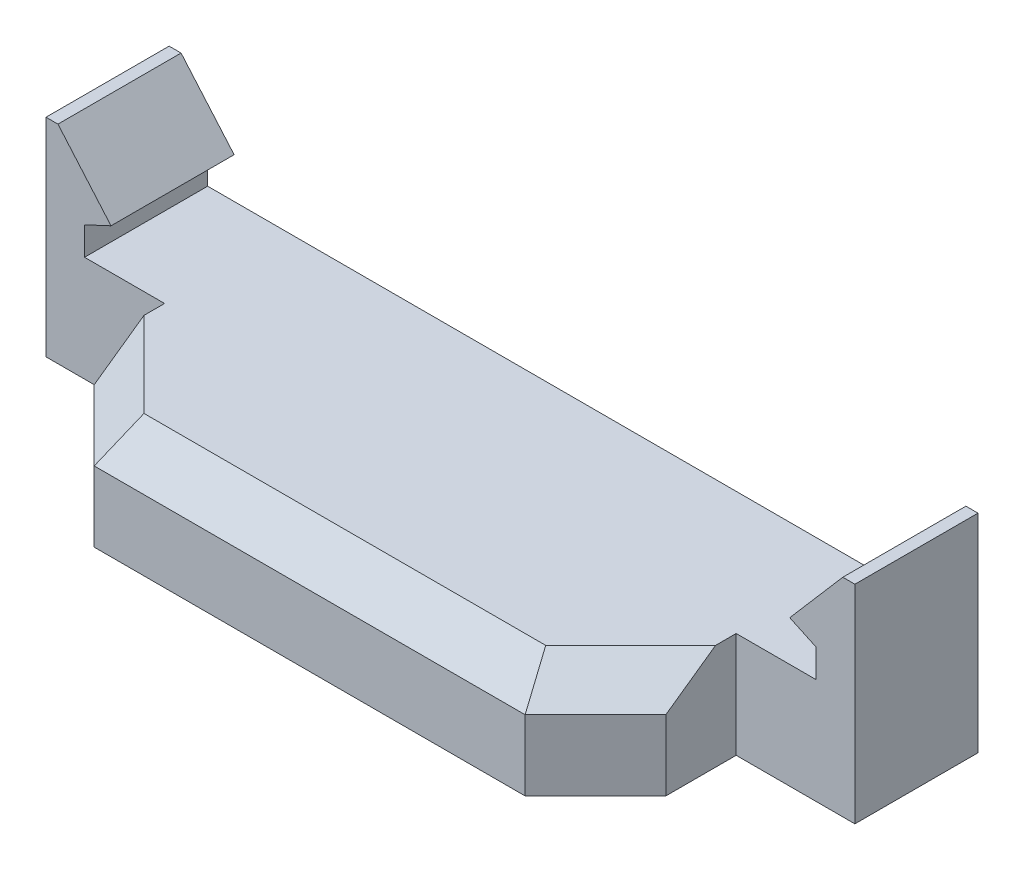
SolidWorks part; units mm, degrees
ref_plane "Plano frontal" through (0, 0, 0) normal (0, 0, 1) x (1, 0, 0)
ref_plane "Plano superior" through (0, 0, 0) normal (0, 1, 0) x (1, 0, 0)
ref_plane "Plano direito" through (0, 0, 0) normal (1, 0, 0) x (0, 0, -1)
sketch "Esboço2" plane through (0, 0, 0) normal (0, 0, 1) x (1, 0, 0)
  line L0 (11.1561, 4.4006) -> (12, 4.4006)
  line L1 (-11.996, 1.5) -> (12.25, 1.5)
  line L2 (-12.25, 1.5) -> (-12.25, -1.5) construction
  line L3 (-11.996, -1.5) -> (12, -1.5)
  line L4 (12.25, 1.5) -> (12.25, -1.5) construction
  line L5 (-12.25, 1.5) -> (12.25, -1.5) construction
  line L6 (-12.25, -1.5) -> (12.25, 1.5) construction
  line L7 (11.1561, 4.4006) -> (9.6482, 2.6506)
  line L8 (9.6482, 2.6506) -> (10.4, 2.3)
  line L9 (10.4, 2.3) -> (10.4, 1.5)
  line L10 (10.4, 2.3) -> (7.7733, 2.3) construction
  line L11 (0, -9.2019) -> (0, 6.2019) construction
  line L12 (12.25, 4.2917) -> (12.25, 1.5) construction
  line L13 (-10.4, 2.3) -> (-7.7733, 2.3) construction
  line L14 (-12.25, 4.2917) -> (-12.25, 1.5) construction
  line L15 (-10.4, 2.3) -> (-10.4, 1.5)
  line L16 (-9.6482, 2.6506) -> (-10.4, 2.3)
  line L17 (-11.1561, 4.4006) -> (-9.6482, 2.6506)
  line L18 (12.25, 1.5) -> (12.25, -1.5) construction
  line L19 (-11.1561, 4.4006) -> (-11.996, 4.4006)
  line L20 (12, -1.5) -> (12, 4.4006)
  line L21 (-11.996, -1.5) -> (-11.996, 4.4006)
  point P0 (0, 0)
  point P14 (0, -1.5)
  point P24 (0, 0)
  point P25 (9.6482, 2.6506)
  dimension "D1" = 3.1
  dimension "D2" = 24.5
  dimension "D3" = 25
  dimension "D4" = 3
  dimension "D5" = 2.31
  dimension "D6" = 0.8
  dimension "D7" = 1.85
  dimension "D8" = 0.25
  dimension "D9" = 0.254
extrude "Ressalto-extrusão1" add sketch "Esboço2" along normal blind 3.5
sketch "Esboço3" plane through (12, 0, 0) normal (1, 0, 0) x (0, 0, -1)
  line L4 (0, -1.5) -> (0, 4.4006)
  line L5 (0, 4.4006) -> (-3.5, 4.4006)
  line L6 (-3.5, 4.4006) -> (-3.5, -1.5)
  line L7 (-3.5, -1.5) -> (0, -1.5)
  line L8 (0, -1.5) -> (0, 4.4006)
  line L9 (0, 4.4006) -> (-3.5, 4.4006)
  line L10 (-3.5, 4.4006) -> (-3.5, -1.5)
  line L11 (-3.5, -1.5) -> (0, -1.5)
  dimension "D1" = 0
extrude "Corte-extrusão1" cut sketch "Esboço3" against normal blind 0.5
sketch "Esboço4" plane through (-11.996, 0, 0) normal (-1, 0, 0) x (0, 0, 1)
  line L4 (0, 4.4006) -> (0, -1.5)
  line L5 (0, -1.5) -> (3.5, -1.5)
  line L6 (3.5, -1.5) -> (3.5, 4.4006)
  line L7 (3.5, 4.4006) -> (0, 4.4006)
  line L8 (0, 4.4006) -> (0, -1.5)
  line L9 (0, -1.5) -> (3.5, -1.5)
  line L10 (3.5, -1.5) -> (3.5, 4.4006)
  line L11 (3.5, 4.4006) -> (0, 4.4006)
  dimension "D1" = 0
extrude "Corte-extrusão2" cut sketch "Esboço4" against normal blind 0.5
sketch "Esboço5" plane through (0, 0, 3.5) normal (0, 0, 1) x (1, 0, 0)
  line L0 (-11.496, -1.5) -> (11.5, -1.5) construction
  line L1 (-8.125, 1.5) -> (8.125, 1.5)
  line L2 (-8.125, 1.5) -> (-8.125, -1.5)
  line L3 (-8.125, -1.5) -> (8.125, -1.5)
  line L4 (8.125, 1.5) -> (8.125, -1.5)
  line L5 (-8.125, 1.5) -> (8.125, -1.5) construction
  line L6 (-8.125, -1.5) -> (8.125, 1.5) construction
  point P0 (0, 0)
  dimension "D1" = 16.25
extrude "Ressalto-extrusão2" add sketch "Esboço5" along normal blind 4
sketch "Esboço6" plane through (0, 0, 0) normal (0, 0, -1) x (-1, 0, 0)
  line L1 (-8.125, 1.5) -> (8.125, 1.5)
  line L2 (-8.125, 1.5) -> (-8.125, -1.5)
  line L3 (-8.125, -1.5) -> (8.125, -1.5)
  line L4 (8.125, 1.5) -> (8.125, -1.5)
  line L5 (-8.125, 1.5) -> (8.125, -1.5) construction
  line L6 (-8.125, -1.5) -> (8.125, 1.5) construction
  point P0 (0, 0)
extrude "Ressalto-extrusão3" [suppressed] add sketch "Esboço6" along normal blind 4
chamfer "Chanfro1" distance 2 angle 45 2 edges at (-8.125, 0, 7.5) (8.125, 0, 7.5)
chamfer "Chanfro4" distance 1 angle 45 3 edges at (7.125, 1.5, 6.5) (-7.125, 1.5, 6.5) (0, 1.5, 7.5)
